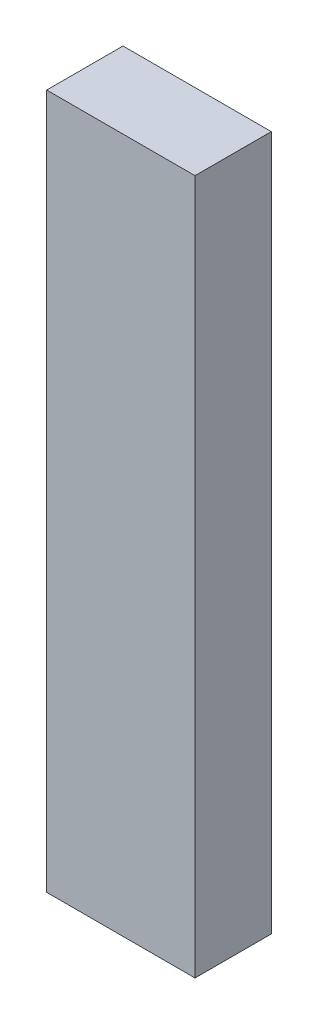
SolidWorks part; units mm, degrees
ref_plane "Front Plane" through (0, 0, 0) normal (0, 0, 1) x (1, 0, 0)
ref_plane "Top Plane" through (0, 0, 0) normal (0, 1, 0) x (1, 0, 0)
ref_plane "Right Plane" through (0, 0, 0) normal (1, 0, 0) x (0, 0, -1)
sketch "Sketch1" plane through (0, 0, 0) normal (0, 0, 1) x (1, 0, 0)
  line L1 (-17.5, 82) -> (17.5, 82)
  line L2 (-17.5, 82) -> (-17.5, -82)
  line L3 (-17.5, -82) -> (17.5, -82)
  line L4 (17.5, 82) -> (17.5, -82)
  line L5 (-17.5, 82) -> (17.5, -82) construction
  line L6 (-17.5, -82) -> (17.5, 82) construction
  point P0 (0, 0)
  dimension "D1" = 35
  dimension "D2" = 164
extrude "Boss-Extrude1" add sketch "Sketch1" along normal blind 18
